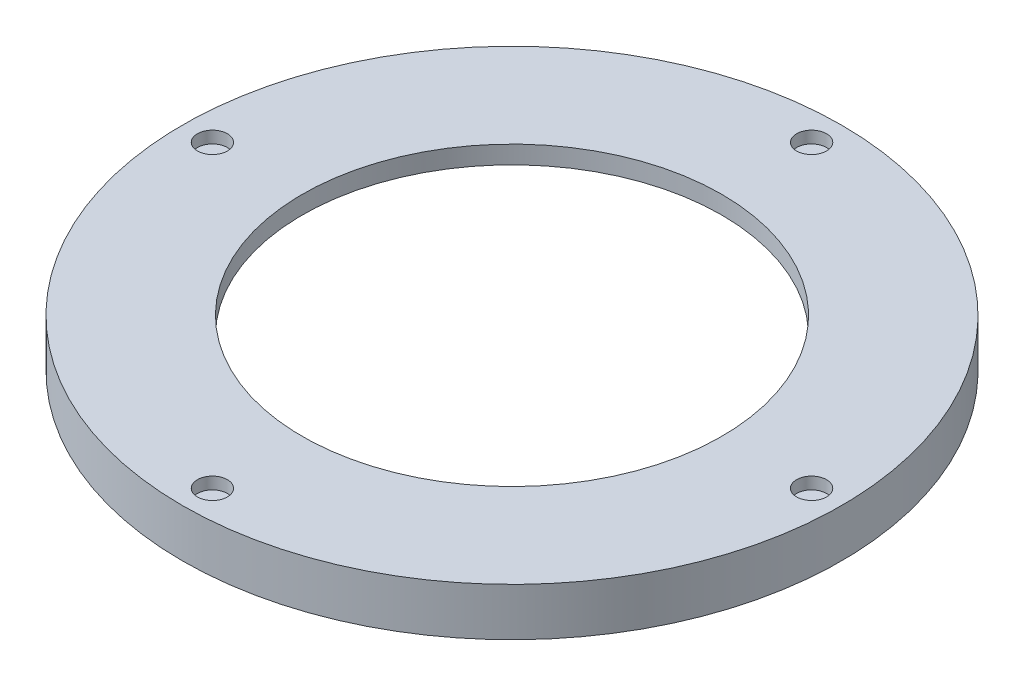
SolidWorks part; units mm, degrees
ref_plane "Front Plane" through (0, 0, 0) normal (0, 0, 1) x (1, 0, 0)
ref_plane "Top Plane" through (0, 0, 0) normal (0, 1, 0) x (1, 0, 0)
ref_plane "Right Plane" through (0, 0, 0) normal (1, 0, 0) x (0, 0, -1)
sketch "Sketch1" plane through (0, 0, 0) normal (0, 1, 0) x (1, 0, 0)
  circle A0 centre (0, 0) radius 27.5
  dimension "D1" = 55
extrude "Boss-Extrude1" add sketch "Sketch1" along normal blind 4
sketch "Sketch2" plane through (0, 4, 0) normal (0, 1, 0) x (1, 0, 0)
  line L0 (0, -25) -> (0, 25) construction
  line L1 (25, 0) -> (-25, 0) construction
  circle A0 centre (0, 0) radius 25 construction
  circle A1 centre (0, 0) radius 27.5 construction
  circle A2 centre (0, 25) radius 1.25
  circle A3 centre (25, 0) radius 1.25
  circle A4 centre (0, -25) radius 1.25
  circle A5 centre (-25, 0) radius 1.25
  dimension "D1" = 2.5
  dimension "D2" = 2.5
  dimension "D3" = 50
extrude "Cut-Extrude1" cut sketch "Sketch2" against normal blind 1
sketch "Sketch3" plane through (0, 0, 0) normal (0, -1, 0) x (-1, 0, 0)
  circle A0 centre (0, 0) radius 25
  dimension "D1" = 50
extrude "Cut-Extrude5" cut sketch "Sketch3" against normal blind 2.5
sketch "Sketch4" plane through (0, 2.5, 0) normal (0, -1, 0) x (-1, 0, 0)
  circle A0 centre (0, 0) radius 17.5
  dimension "D1" = 35
extrude "Cut-Extrude6" cut sketch "Sketch4" against normal through all
